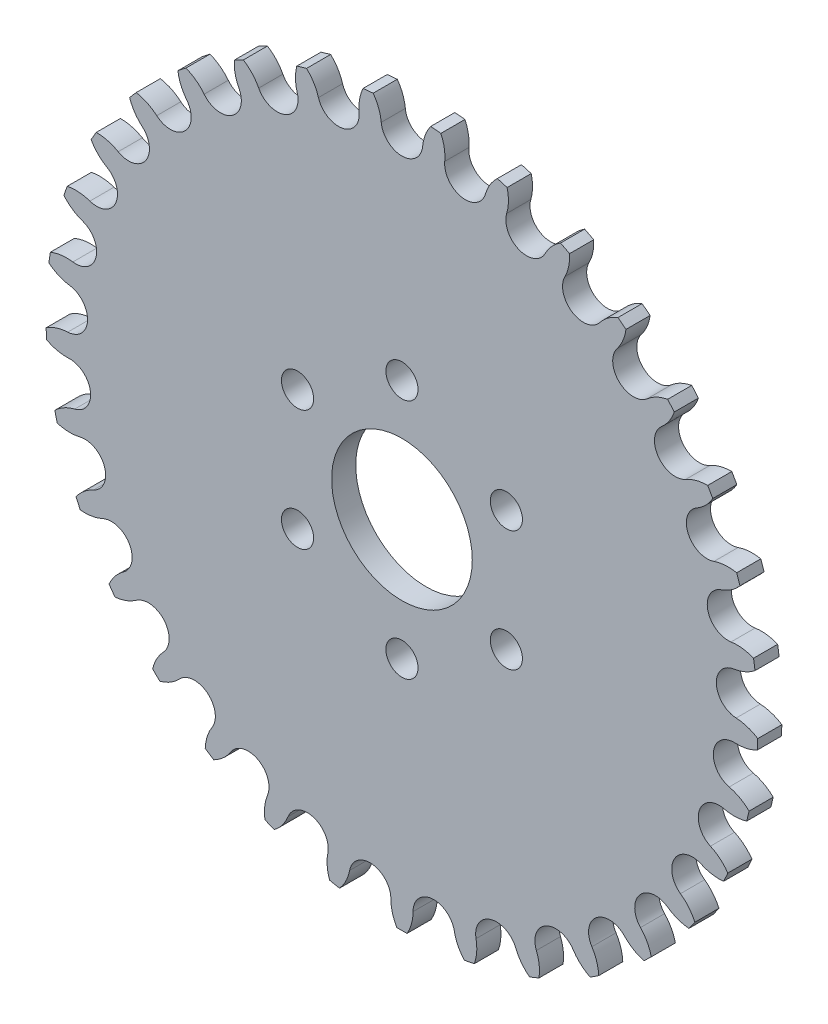
SolidWorks part; units mm, degrees
material "AISI 1020"
ref_plane "Спереди" through (0, 0, 0) normal (0, 0, 1) x (1, 0, 0)
ref_plane "Сверху" through (0, 0, 0) normal (0, 1, 0) x (1, 0, 0)
ref_plane "Справа" through (0, 0, 0) normal (1, 0, 0) x (0, 0, -1)
sketch "Эскиз1" plane through (0, 0, 0) normal (0, 0, 1) x (1, 0, 0)
  line L0 (0, 0) -> (0, 85) construction
  line L1 (0, 85) -> (15.8056, 83.5176) construction
  line L2 (15.8056, 83.5176) -> (0, 0) construction
  line L3 (15.8056, 83.5176) -> (49.3989, 83.5176)
  line L4 (0, 0) -> (0, 83.5034)
  line L5 (0, 83.5034) -> (15.8031, 81.9944)
  line L6 (15.8031, 81.9944) -> (0, 0)
  circle A0 centre (0, 0) radius 85 construction
  circle A1 centre (0, 83.5034) radius 5.08
  circle A2 centre (15.8031, 81.9944) radius 5.08
  dimension "D1" = 170
  dimension "D6" = 10.16
  dimension "D2" = 15.875
  dimension "D3" = 10.716
  dimension "D4" = 33.5932
  dimension "D5" = 10.909
sketch "Эскиз2" plane through (0, 0, 0) normal (0, 0, 1) x (1, 0, 0)
  line L0 (0, 0) -> (0, 78.3234)
  line L1 (0, 0) -> (14.8228, 76.908)
  line L4 (15.8031, 81.9944) -> (0, 0) construction
  arc A0 (10.6466, 82.4867) -> (9.679, 88.053) centre (0, 83.5034) ccw
  arc A1 (0, 88.5834) -> (16.7645, 86.9826) centre (0, 0) cw construction
  circle A2 centre (0, 83.5034) radius 5.08 construction
  circle A3 centre (15.8031, 81.9944) radius 5.08 construction
  circle A4 centre (0, 0) radius 85 construction
  circle A5 centre (0, 83.5034) radius 5.18
  arc A6 (0, 78.3234) -> (5.1565, 83.011) centre (0, 83.5034) ccw
  arc A7 (7.16, 88.2935) -> (5.1565, 83.011) centre (15.8031, 81.9944) ccw
  circle A8 centre (15.8031, 81.9944) radius 5.18
  arc A9 (10.6466, 82.4867) -> (14.8228, 76.908) centre (15.8031, 81.9944) ccw
  arc A10 (7.16, 88.2935) -> (9.679, 88.053) centre (0, 0) cw
  dimension "D1" = 0.1
  dimension "D2" = 0.1
extrude "Бобышка-Вытянуть1" add sketch "Эскиз2" along normal blind 6
pattern_circular "Круговой массив1" count 33 over 360 about axis through (0, 0, 0) along (0, 0, 1) of "Бобышка-Вытянуть1"
sketch "Эскиз3" plane through (0, 0, 6) normal (0, 0, 1) x (1, 0, 0)
  line L0 (0, 0) -> (0, 30) construction
  line L1 (0, 0) -> (25.9808, 15) construction
  circle A0 centre (0, 0) radius 17.5
  circle A1 centre (0, 0) radius 30 construction
  circle A2 centre (0, 30) radius 4
  circle A3 centre (25.9808, 15) radius 4
  circle A4 centre (25.9808, -15) radius 4
  circle A5 centre (0, -30) radius 4
  circle A6 centre (-25.9808, -15) radius 4
  circle A7 centre (-25.9808, 15) radius 4
  dimension "D1" = 35
  dimension "D2" = 60
  dimension "D3" = 8
  dimension "D5" = 60
  dimension "D6" = 30
  dimension "D4" = 6
extrude "Вырез-Вытянуть1" cut sketch "Эскиз3" against normal through all
equation "\"D4@Эскиз1\"=360/\"D3@Эскиз1\""
equation "\"D5@Эскиз1\"=360/33"
